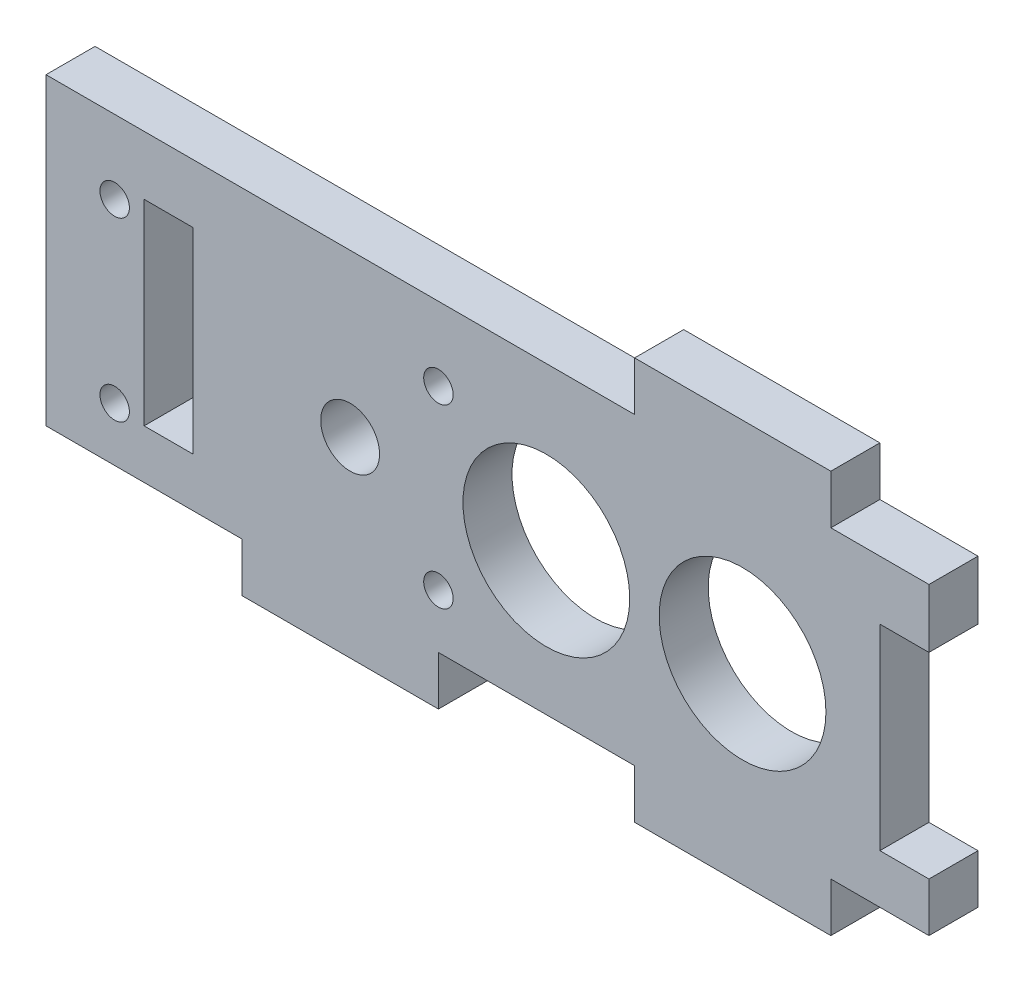
SolidWorks part; units mm, degrees
ref_plane "Front Plane" through (0, 0, 0) normal (0, 0, 1) x (1, 0, 0)
ref_plane "Top Plane" through (0, 0, 0) normal (0, 1, 0) x (1, 0, 0)
ref_plane "Right Plane" through (0, 0, 0) normal (1, 0, 0) x (0, 0, -1)
sketch "Sketch2" plane through (0, 0, 0) normal (0, 0, 1) x (1, 0, 0)
  line L0 (0, 31) -> (0, 14.5)
  line L1 (0, 0) -> (10, 0)
  line L2 (0, 0) -> (0, 31)
  line L3 (0, 31) -> (50, 31)
  line L4 (80, 0) -> (80, 5)
  line L5 (0, 14.5) -> (75, 14.5)
  line L6 (0, 14.5) -> (21, 14.5)
  line L7 (21, 14.5) -> (41, 14.5)
  line L8 (41, 14.5) -> (61, 14.5)
  line L9 (21, 14.5) -> (21, 23.5)
  line L10 (0, 5) -> (5, 5)
  line L11 (0, 5) -> (0, 25)
  line L12 (70, 31) -> (80, 31)
  line L13 (5, 5) -> (5, 23)
  line L14 (30, 23.5) -> (30, 5.5)
  line L15 (30, 0) -> (50, 0)
  line L16 (70, 0) -> (80, 0)
  line L17 (80, 25) -> (75, 25)
  line L18 (75, 25) -> (75, 23)
  line L19 (80, 25) -> (80, 31)
  line L20 (50, 26) -> (70, 26)
  line L24 (80, 5) -> (75, 5)
  line L25 (75, 23) -> (75, 5)
  line L27 (70, 0) -> (70, -5)
  line L28 (70, -5) -> (50, -5)
  line L29 (50, 0) -> (50, -5)
  line L31 (30, 0) -> (30, -5)
  line L32 (10, -5) -> (30, -5)
  line L33 (10, 0) -> (10, -5)
  line L34 (21, 23.5) -> (30, 23.5)
  line L35 (30, 23.5) -> (12, 23.5)
  line L38 (0, 28) -> (0, 23)
  line L39 (0, 23) -> (5, 23)
  line L42 (80, 28) -> (80, 25)
  line L51 (50, 26) -> (70, 26)
  line L52 (50, 31) -> (50, 36)
  line L53 (50, 36) -> (70, 36)
  line L54 (70, 31) -> (70, 36)
  circle A0 centre (21, 14.5) radius 3
  circle A1 centre (41, 14.5) radius 8.5
  circle A2 centre (61, 14.5) radius 8.5
  circle A3 centre (30, 23.5) radius 1.5
  circle A4 centre (30, 5.5) radius 1.5
  dimension "D6" = 6
  dimension "D8" = 17
  dimension "D30" = 3
  dimension "D31" = 3
  dimension "D39" = 17
  dimension "D1" = 80
  dimension "D2" = 31
  dimension "D4" = 20
  dimension "D5" = 20
  dimension "D10" = 5
  dimension "D12" = 5
  dimension "D15" = 20
  dimension "D16" = 20
  dimension "D17" = 5
  dimension "D18" = 5
  dimension "D19" = 10
  dimension "D20" = 10
  dimension "D21" = 16.5
  dimension "D22" = 20
  dimension "D23" = 5
  dimension "D25" = 18
  dimension "D27" = 9
  dimension "D28" = 9
  dimension "D29" = 9
  dimension "D33" = 5
  dimension "D46" = 10
extrude "Boss-Extrude1" add sketch "Sketch2" against normal blind 5
sketch "Sketch3" plane through (0, 0, 0) normal (-1, 0, 0) x (0, 0, 1)
  line L1 (-5, 31) -> (0, 31)
  line L2 (-5, 31) -> (-5, 0)
  line L3 (-5, 0) -> (0, 0)
  line L4 (0, 31) -> (0, 0)
extrude "Boss-Extrude2" add sketch "Sketch3" along normal blind 10
sketch "Sketch4" plane through (0, 0, 0) normal (0, 0, 1) x (1, 0, 0)
  line L0 (-10, 31) -> (50, 31) construction
  line L1 (30, 5.5) -> (-3, 5.5) construction
  line L2 (30, 5.5) -> (30, 23.5) construction
  line L3 (30, 23.5) -> (-3, 23.5) construction
  line L4 (-3, 5.5) -> (-3, 23.5) construction
  line L5 (5, 25) -> (0, 25)
  line L6 (5, 25) -> (5, 5)
  line L7 (5, 5) -> (0, 5)
  line L8 (0, 25) -> (0, 5)
  line L9 (-10, 0) -> (-10, 31) construction
  circle A0 centre (-3, 23.5) radius 1.5
  circle A1 centre (-3, 5.5) radius 1.5
  dimension "D1" = 3
  dimension "D2" = 3
  dimension "D3" = 20
  dimension "D4" = 33
  dimension "D5" = 18
  dimension "D6" = 5
  dimension "D7" = 6
  dimension "D8" = 10
extrude "Cut-Extrude1" cut sketch "Sketch4" against normal blind 10
